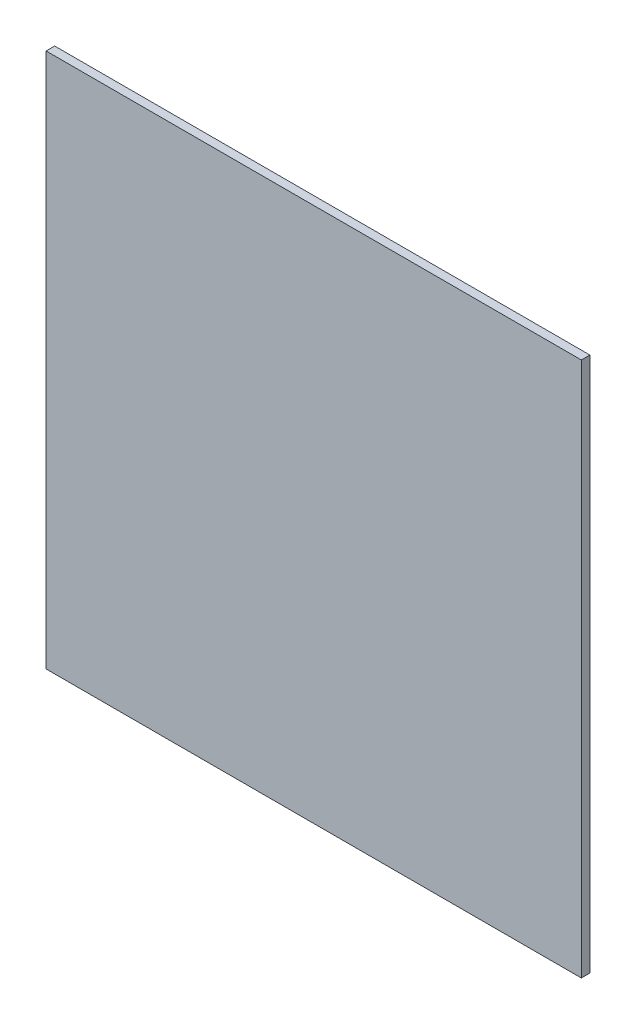
SolidWorks part; units mm, degrees
ref_plane "Front Plane" through (0, 0, 0) normal (0, 0, 1) x (1, 0, 0)
ref_plane "Top Plane" through (0, 0, 0) normal (0, 1, 0) x (1, 0, 0)
ref_plane "Right Plane" through (0, 0, 0) normal (1, 0, 0) x (0, 0, -1)
sketch "Sketch1" plane through (0, 0, 0) normal (0, 0, 1) x (1, 0, 0)
  line L1 (0, 0) -> (100, 0)
  line L2 (0, 0) -> (0, -100)
  line L3 (0, -100) -> (100, -100)
  line L4 (100, 0) -> (100, -100)
  dimension "D1" = 100
  dimension "D2" = 100
extrude "Boss-Extrude1" add sketch "Sketch1" along normal blind 1.6
